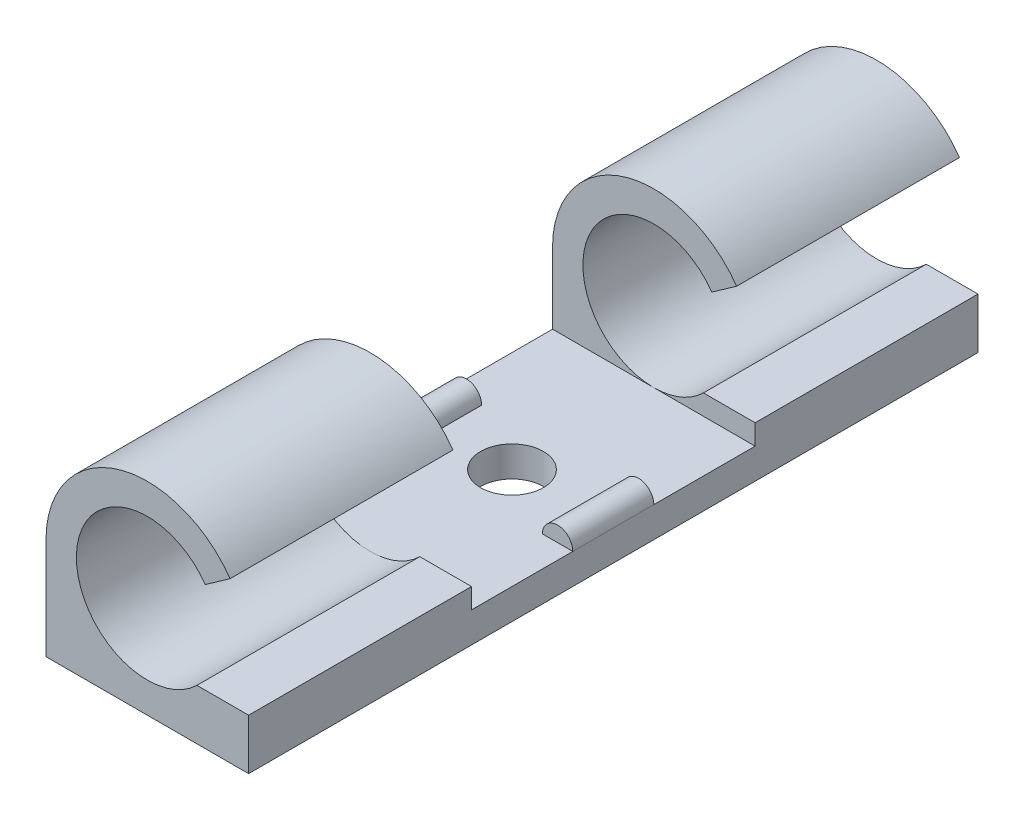
SolidWorks part; units mm, degrees
ref_plane "Plano frontal" through (0, 0, 0) normal (0, 0, 1) x (1, 0, 0)
ref_plane "Plano superior" through (0, 0, 0) normal (0, 1, 0) x (1, 0, 0)
ref_plane "Plano direito" through (0, 0, 0) normal (1, 0, 0) x (0, 0, -1)
sketch "Esboço1" plane through (0, 0, 0) normal (0, 0, 1) x (1, 0, 0)
  line L0 (-5, 0) -> (5, 0)
  line L1 (-5, 5) -> (5, 5)
  line L2 (-5, 5) -> (-5, -5)
  line L3 (-5, -5) -> (5, -5)
  line L4 (5, 5) -> (5, -5)
  line L5 (-5, 5) -> (5, -5) construction
  line L6 (-5, -5) -> (5, 5) construction
  circle A0 centre (0, 0) radius 5
  circle A2 centre (0, 0) radius 3.5
  point P0 (0, 0)
  point P12 (0, 0)
  dimension "D3" = 7
  dimension "D1" = 10
  dimension "D2" = 10
extrude "Ressalto-extrusão1" add sketch "Esboço1" along normal blind 11 contours A0 L2 L3 | A0 L3 L4 | A2 L0 A0 | A2 L0 A0
sketch "Esboço2" plane through (0, 0, 11) normal (0, 0, 1) x (1, 0, 0)
  line L0 (5, 0) -> (5, -5) construction
  line L1 (-5, -5) -> (5, -5)
  line L2 (-5, -5) -> (-5, -3.5)
  line L3 (-5, -3.5) -> (5, -3.5)
  line L4 (5, -5) -> (5, -3.5)
  line L5 (-5, -5) -> (5, -3.5) construction
  line L6 (-5, -3.5) -> (5, -5) construction
  circle A0 centre (0, 0) radius 3.5 construction
  point P4 (0, -4.25)
extrude "Ressalto-extrusão2" add sketch "Esboço2" along normal blind 7
sketch "Esboço3" plane through (0, 0, 18) normal (0, 0, 1) x (1, 0, 0)
  line L0 (5, -3.5) -> (0, -3.5) construction
  line L1 (5, -3.5) -> (0, -3.5) construction
  line L2 (0, 0) -> (0, -0.723) construction
  arc A0 (5, -3.5) -> (3.5, -3.5) centre (4.25, -3.5) ccw
  arc A1 (3.5, -3.5) -> (5, -3.5) centre (4.25, -3.5) ccw construction
  arc A2 (-5, -3.5) -> (-3.5, -3.5) centre (-4.25, -3.5) cw
  line M5 (5, -3.5) -> (-5, -3.5)
  dimension "D1" = 1.5
extrude "Ressalto-extrusão3" add sketch "Esboço3" against normal blind 2 contours A0 M5 | A2 M5
mirror "Espelhar1" about plane through (0, 0, 18) normal (0, 0, -1) of "Ressalto-extrusão2", "Ressalto-extrusão1", "Ressalto-extrusão3"
sketch "Esboço4" plane through (0, -3.5, 0) normal (0, 1, 0) x (1, 0, 0)
  line L0 (0, -11) -> (0, -18) construction
  line L2 (-3.5, -18) -> (3.5, -18) construction
  line L3 (-3.5, -16) -> (-3.5, -20) construction
  line L4 (3.5, -16) -> (3.5, -20) construction
  line L5 (-5, -11) -> (5, -11) construction
  circle A0 centre (0, -18) radius 1.55
  point P2 (0, 0)
  point P13 (0, -17.7766)
  dimension "D1" = 3.1
extrude "Corte-extrusão1" cut sketch "Esboço4" against normal blind 2
sketch "Esboço5" plane through (0, 0, 36) normal (0, 0, 1) x (1, 0, 0)
  line L0 (5, -2.5) -> (2.4495, -2.5)
  line L1 (5, 0) -> (5, -5) construction
  line L2 (-5, -5) -> (5, -5) construction
  line L3 (4.5826, 2) -> (2.839, 2) construction
  line L4 (2.839, 2) -> (4.0875, 2.8796)
  line L5 (0, 0) -> (2.839, 2) construction
  circle A0 centre (0, 0) radius 3.5 construction
  arc A1 (5, 0) -> (-5, 0) centre (0, 0) ccw construction
  circle M4 centre (0, 0) radius 3.5
  line M6 (5, -5) -> (5, 0)
  arc M7 (5, 0) -> (-5, 0) centre (0, 0) ccw
  dimension "D1" = 2.5
  dimension "D2" = 4.5
  dimension "D3" = 35.164
extrude "Corte-extrusão2" cut sketch "Esboço5" against normal through all contours L4 L0 M4 M6 M7
equation "\"D2@Esboço1\"=\"D1@Esboço1\""
equation "\"D3@Esboço1\"=\"D1@Esboço1\"-3"
